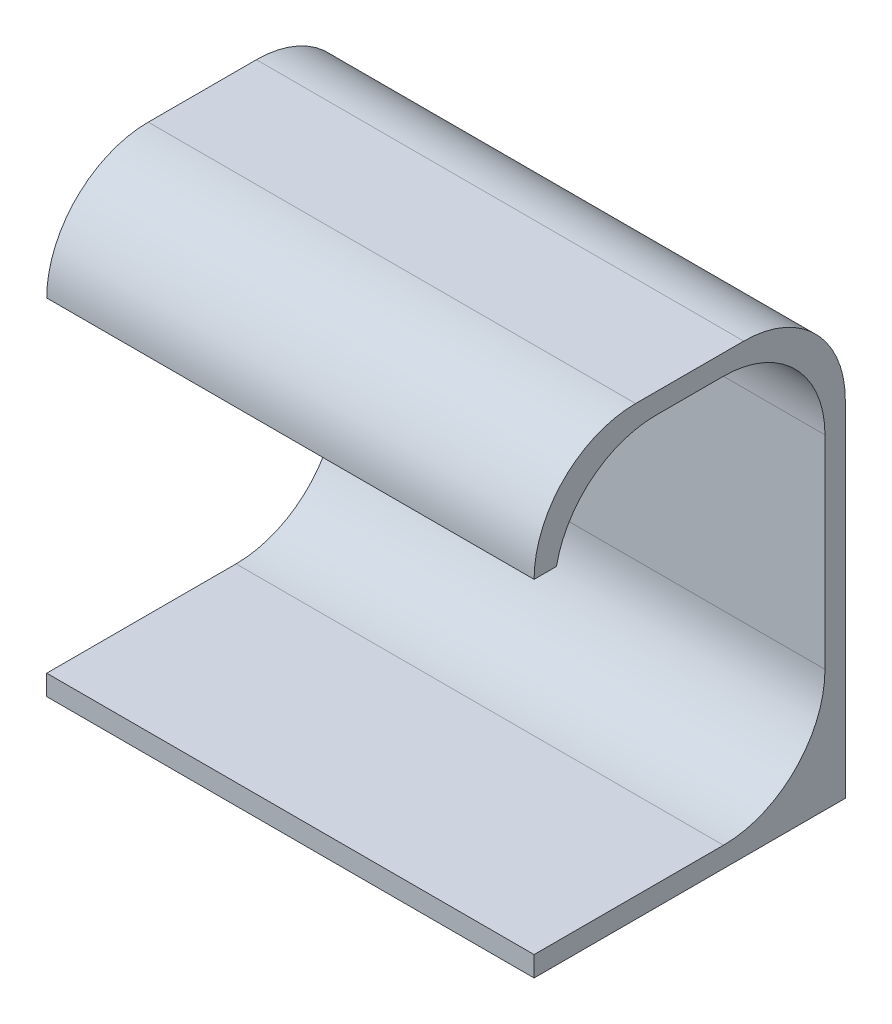
SolidWorks part; units mm, degrees
ref_plane "Front Plane" through (0, 0, 0) normal (0, 0, 1) x (1, 0, 0)
ref_plane "Top Plane" through (0, 0, 0) normal (0, 1, 0) x (1, 0, 0)
ref_plane "Right Plane" through (0, 0, 0) normal (1, 0, 0) x (0, 0, -1)
sketch "Sketch3" plane through (0, 0, 0) normal (1, 0, 0) x (0, 0, -1)
  line L0 (0, 0) -> (0, -20.3) construction
  line L1 (0, -20.3) -> (7.25, -20.3) construction
  line L2 (7.25, -20.3) -> (7.25, -11.0343)
  line L3 (7.25, -11.0343) -> (7.25, -2)
  line L4 (17.25, 8) -> (27.9, 8)
  line L5 (37.9, -2) -> (37.9, -20.3)
  line L6 (37.9, -20.3) -> (7.25, -20.3) construction
  line L7 (37.9, -20.3) -> (37.9, -36)
  line L8 (37.9, -36) -> (7.25, -36)
  line L9 (7.25, -36) -> (7.25, -20.3)
  line L10 (9.25, -20.3) -> (9.25, -11.0343)
  line L11 (9.25, -11.0343) -> (9.25, -4)
  line L12 (19.25, 6) -> (25.9, 6)
  line L13 (35.9, -4) -> (35.9, -20.3)
  line L14 (35.9, -20.3) -> (35.9, -24)
  line L15 (25.9, -34) -> (9.25, -34)
  line L16 (9.25, -34) -> (9.25, -20.3)
  line L17 (35.9, -20.3) -> (35.9, -34) construction
  line L18 (35.9, -34) -> (9.25, -34) construction
  line L19 (7.25, 8) -> (37.9, 8) construction
  line L20 (37.9, 8) -> (37.9, -20.3) construction
  line L21 (9.25, 6) -> (35.9, 6) construction
  line L22 (35.9, 6) -> (35.9, -20.3) construction
  line L23 (7.25, -11.0343) -> (7.25, 8) construction
  line L24 (9.25, -11.0343) -> (9.25, 6) construction
  arc A0 (35.9, -24) -> (25.9, -34) centre (25.9, -24) cw
  arc A1 (27.9, 8) -> (37.9, -2) centre (27.9, -2) cw
  arc A2 (25.9, 6) -> (35.9, -4) centre (25.9, -4) cw
  arc A3 (7.25, -2) -> (17.25, 8) centre (17.25, -2) cw
  arc A4 (9.25, -4) -> (19.25, 6) centre (19.25, -4) cw
  point P23 (37.9, 8)
  point P33 (0, 0)
  dimension "D1" = 28.3
  dimension "D5" = 10
  dimension "D2" = 15.7
  dimension "D3" = 20.3
  dimension "D4" = 2
extrude "Boss-Extrude3" add sketch "Sketch3" along normal blind 48
sketch "Sketch4" plane through (0, 0, 0) normal (-1, 0, 0) x (0, 0, 1)
  line L0 (-9.25, -34) -> (-7.25, -34)
  line L1 (-7.25, -2) -> (-7.25, -36) construction
  line L2 (-7.25, -34) -> (-7.25, -2)
  line L3 (-7.25, -2) -> (-9.452, -2)
  line L4 (-9.452, -2) -> (-9.25, -34)
  arc A0 (-9.25, -4) -> (-19.25, 6) centre (-19.25, -4) ccw construction
  dimension "D1" = 2.202
  dimension "D2" = 2
  dimension "D3" = 32
extrude "Cut-Extrude2" cut sketch "Sketch4" against normal blind 54
